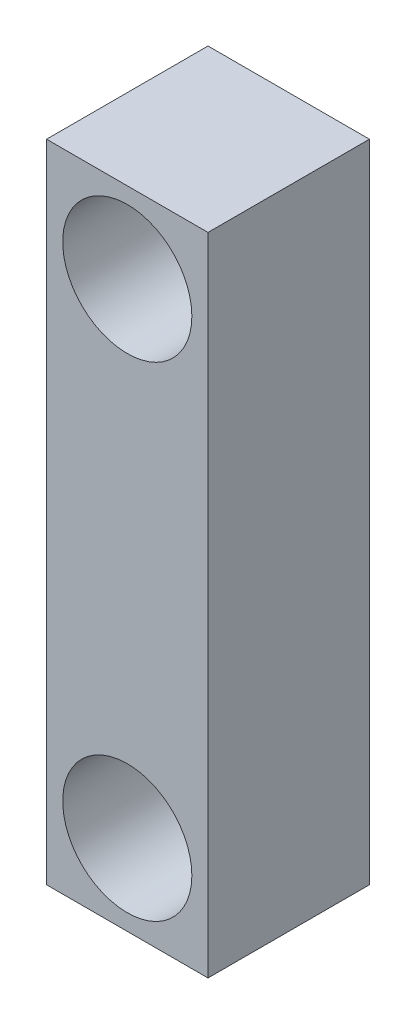
SolidWorks part; units mm, degrees
material "AISI 1020"
ref_plane "Front" through (0, 0, 0) normal (0, 0, 1) x (1, 0, 0)
ref_plane "Top" through (0, 0, 0) normal (0, 1, 0) x (1, 0, 0)
ref_plane "Right" through (0, 0, 0) normal (1, 0, 0) x (0, 0, -1)
sketch "Sketch1" plane through (0, 0, 0) normal (0, 0, 1) x (1, 0, 0)
  line L1 (-12.7, 50.8) -> (12.7, 50.8)
  line L2 (-12.7, 50.8) -> (-12.7, -50.8)
  line L3 (-12.7, -50.8) -> (12.7, -50.8)
  line L4 (12.7, 50.8) -> (12.7, -50.8)
  line L5 (-12.7, 50.8) -> (12.7, -50.8) construction
  line L6 (-12.7, -50.8) -> (12.7, 50.8) construction
  point P0 (0, 0)
  dimension "D1" = 25.4
  dimension "D2" = 101.6
extrude "Boss-Extrude1" add sketch "Sketch1" along normal blind 25.4
sketch "Sketch2" plane through (0, 0, 25.4) normal (0, 0, 1) x (1, 0, 0)
  line L0 (12.7, -50.8) -> (12.7, 50.8) construction
  line L1 (-12.7, -50.8) -> (12.7, -50.8) construction
  line L2 (12.7, 50.8) -> (-12.7, 50.8) construction
  circle A0 centre (0, -38.1) radius 10.16
  circle A1 centre (0, 38.1) radius 10.16
  dimension "D1" = 20.32
  dimension "D2" = 20.32
  dimension "D3" = 12.7
  dimension "D4" = 12.7
  dimension "D5" = 12.7
  dimension "D6" = 12.7
extrude "Cut-Extrude1" cut sketch "Sketch2" against normal blind 25.4
scale "Scale1" scale about centroid uniform scaling yes scale factor 3
